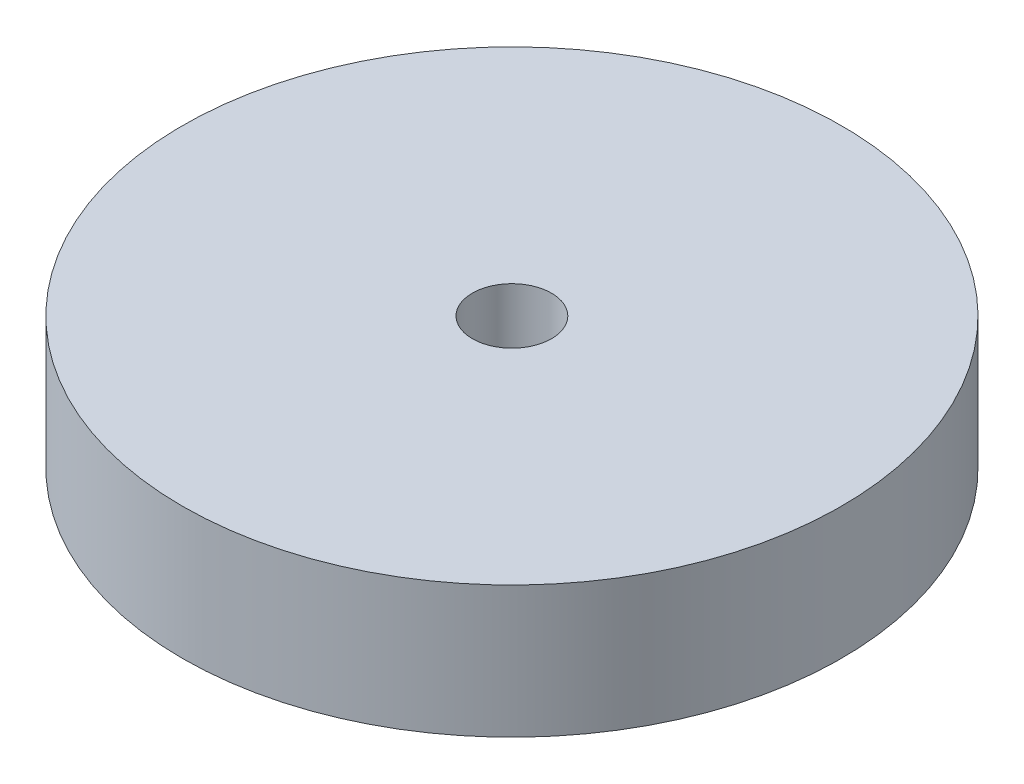
SolidWorks part; units mm, degrees
material "Plain Carbon Steel"
ref_plane "Front Plane" through (0, 0, 0) normal (0, 0, 1) x (1, 0, 0)
ref_plane "Top Plane" through (0, 0, 0) normal (0, 1, 0) x (1, 0, 0)
ref_plane "Right Plane" through (0, 0, 0) normal (1, 0, 0) x (0, 0, -1)
sketch "Sketch1" plane through (0, 0, 0) normal (0, 1, 0) x (1, 0, 0)
  circle A0 centre (0, 0) radius 25
  circle A1 centre (0, 0) radius 3
  dimension "D1" = 50
  dimension "D2" = 6
extrude "Boss-Extrude1" add sketch "Sketch1" along normal mid plane 10
